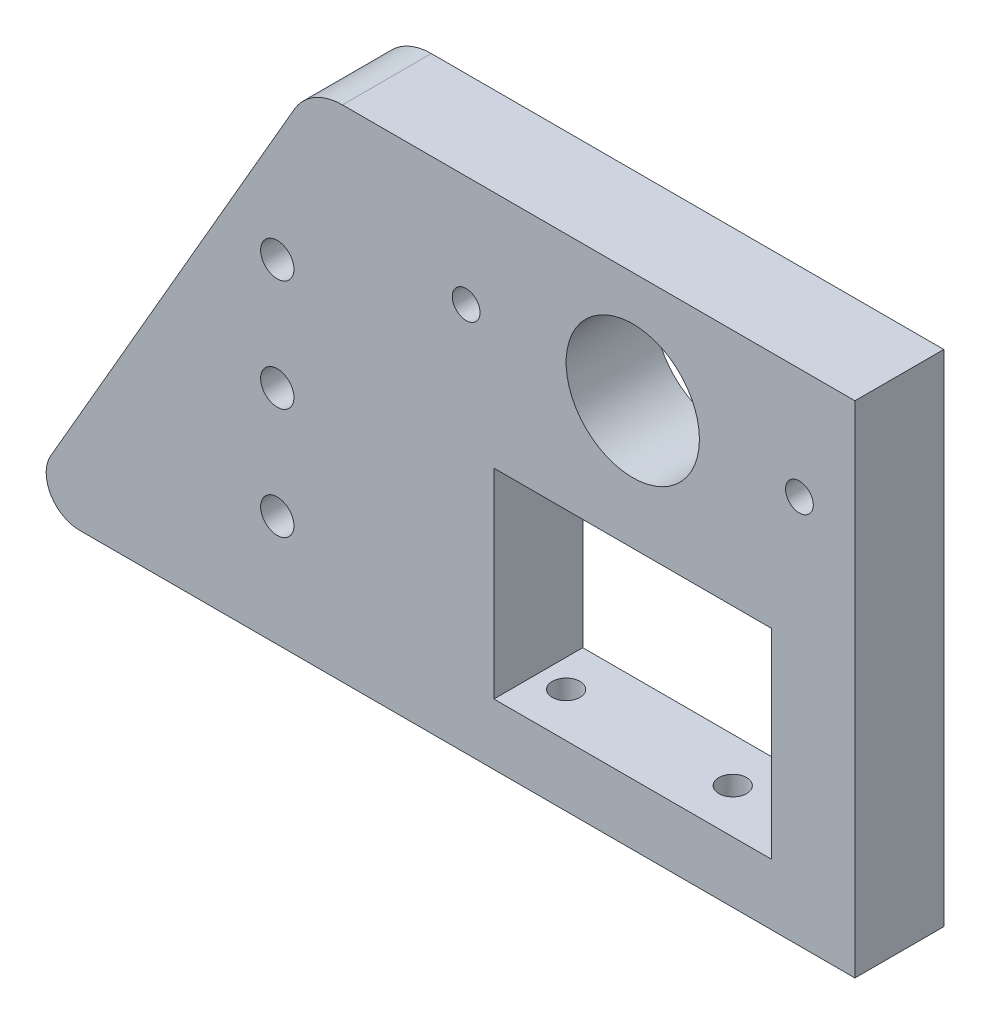
SolidWorks part; units mm, degrees
ref_plane "前基準面" through (0, 0, 0) normal (0, 0, 1) x (1, 0, 0)
ref_plane "上基準面" through (0, 0, 0) normal (0, 1, 0) x (1, 0, 0)
ref_plane "右基準面" through (0, 0, 0) normal (1, 0, 0) x (0, 0, -1)
sketch "草圖1" plane through (0, 0, 0) normal (0, 0, 1) x (1, 0, 0)
  line L0 (0, 0) -> (0, 10) construction
  line L4 (-52.4019, -30.5) -> (-30.4626, 7.5)
  line L5 (-26.1325, 10) -> (0, 10)
  line L21 (0, 10) -> (20, 10)
  line L22 (-49.8038, -35) -> (0, -35)
  line L29 (0, 0) -> (0, -35) construction
  line L30 (20, 10) -> (20, -35)
  line L31 (20, -35) -> (0, -35)
  line L32 (0, -35) -> (-32, -35)
  line L33 (-32, -35) -> (-32, -25) construction
  line L34 (-32, -25) -> (-32, -15) construction
  line L35 (-32, -15) -> (-32, -5) construction
  line L40 (0, 0) -> (0, -20.5)
  line L42 (12.5, -29.5) -> (-12.5, -29.5)
  line L43 (12.5, -29.5) -> (12.5, -11.5)
  line L44 (12.5, -11.5) -> (-12.5, -11.5)
  line L45 (-12.5, -29.5) -> (-12.5, -11.5)
  line L46 (12.5, -29.5) -> (-12.5, -11.5) construction
  line L47 (12.5, -11.5) -> (-12.5, -29.5) construction
  arc A3 (-30.4626, 7.5) -> (-26.1325, 10) centre (-26.1325, 5) cw
  arc A5 (-49.8038, -35) -> (-52.4019, -30.5) centre (-49.8038, -32) cw
  circle A6 centre (0, 0) radius 6
  circle A7 centre (-32, -5) radius 1.5
  circle A8 centre (-32, -15) radius 1.5
  circle A9 centre (-32, -25) radius 1.5
  point P11 (-55, -35)
  dimension "D9" = 32
  dimension "D10" = 10
  dimension "D13" = 25
  dimension "D14" = 5
  dimension "D6" = 12
  dimension "D8" = 3
  dimension "D11" = 3
  dimension "D2" = 55
  dimension "D3" = 35
  dimension "D4" = 10
  dimension "D5" = 60
  dimension "D7" = 20
  dimension "D12" = 20.5
  dimension "D15" = 18
extrude "填料-伸長1" add sketch "草圖1" along normal blind 8
ref_plane "平面2" through (0, -35, 0) normal (0, -1, 0) x (-1, 0, 0)
sketch "草圖2" plane through (0, -35, 0) normal (0, -1, 0) x (-1, 0, 0)
  line L0 (-20, -8) -> (-20, -4)
  line L1 (-20, -8) -> (-20, 0) construction
  line L2 (49.8038, -8) -> (-20, -8) construction
  line L3 (-20, -4) -> (-5, -4) construction
  line L4 (-5, -4) -> (10, -4) construction
  line L5 (10, -4) -> (25, -4) construction
  circle A0 centre (-5, -4) radius 1.3
  circle A1 centre (10, -4) radius 1.3
  circle A2 centre (25, -4) radius 1.3
  dimension "D2" = 2.6
  dimension "D1" = 15
hole_wizard "M3 螺紋孔1" positions "3D草圖2" profile "草圖3" tap size "M3" standard "ISO"
sketch3d "3D草圖2"
  point P0 (5, -35, 4)
  point P3 (5, -35, 4)
  point P5 (5, -35, 4)
  point P7 (-10, -35, 4)
  point P10 (-25, -35, 4)
  point P12 (-10, -35, 4)
  point P19 (5, -35, 4)
  point P23 (-10, -35, 4)
  point P25 (-10, -35, 4)
sketch "草圖3" plane through (-10, -35, 4) normal (1, 0, 0) x (0, 0, -1)
  line L0 (0, 0) -> (0, 7.5)
  line L1 (0, 7.5) -> (1.25, 6.7489)
  line L2 (1.25, 6.7489) -> (1.25, 0.6639)
  line L3 (1.25, 0.6639) -> (1.525, 0)
  line L5 (1.525, 0) -> (0, 0)
  line L6 (-1.25, 0.6639) -> (-1.525, 0) construction
  line L10 (0, 7.5) -> (-1.25, 6.7489) construction
  line L11 (0, -6.35) -> (0, 107.95) construction
  dimension "螺孔鑽直徑" = 2.5
  dimension "螺孔鑽深度" = 7.5
  dimension "近端錐孔直徑" = 3.05
  dimension "近端錐孔角度" = 45
  dimension "導頭角度" = 118
ref_plane "平面3" through (0, 0, 0) normal (0, 0, -1) x (-1, 0, 0)
sketch "草圖4" plane through (0, 0, 0) normal (0, 0, -1) x (-1, 0, 0)
  line L0 (0, 0) -> (15, 0) construction
  line L1 (0, 0) -> (-15, 0) construction
  circle A0 centre (-15, 0) radius 1.3
  circle A1 centre (15, 0) radius 1.3
  dimension "D2" = 2.6
  dimension "D1" = 15
hole_wizard "M3 螺紋孔2" positions "3D草圖3" profile "草圖5" tap size "M3" standard "ISO" end condition through all
sketch3d "3D草圖3"
  point P0 (15, 0, 0)
  point P3 (-15, 0, 0)
  point P6 (-15, 0, 0)
  point P8 (-15, 0, 0)
  point P10 (15, 0, 0)
sketch "草圖5" plane through (15, 0, 0) normal (1, 0, 0) x (0, 1, 0)
  line L0 (0, 0) -> (0, 8)
  line L1 (0, 8) -> (1.25, 8)
  line L2 (1.25, 8) -> (1.25, 0.6639)
  line L3 (1.25, 0.6639) -> (1.525, 0)
  line L5 (1.525, 0) -> (0, 0)
  line L6 (-1.25, 0.6639) -> (-1.525, 0) construction
  line L11 (0, -6.35) -> (0, 107.95) construction
  dimension "貫穿螺孔鑽直徑" = 2.5
  dimension "貫穿螺孔鑽深度" = 8
  dimension "近端錐孔直徑" = 3.05
  dimension "近端錐孔角度" = 45
